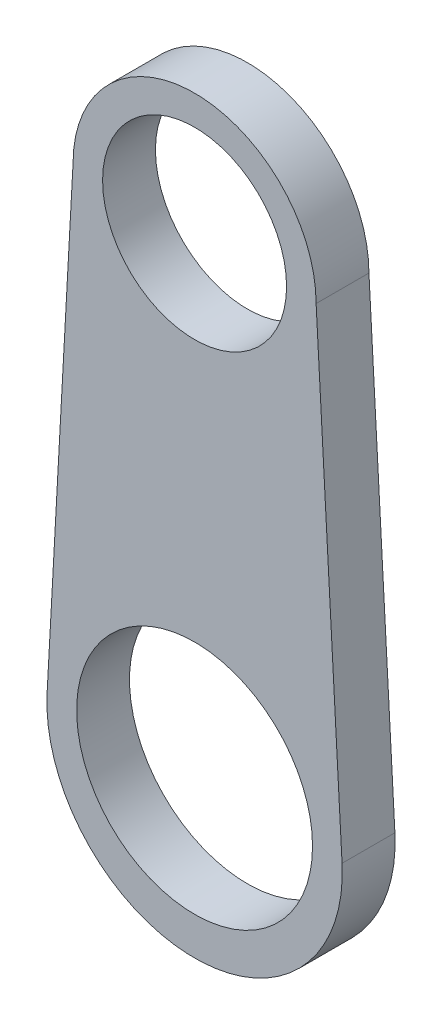
SolidWorks part; units mm, degrees
ref_plane "Front Plane" through (0, 0, 0) normal (0, 0, 1) x (1, 0, 0)
ref_plane "Top Plane" through (0, 0, 0) normal (0, 1, 0) x (1, 0, 0)
ref_plane "Right Plane" through (0, 0, 0) normal (1, 0, 0) x (0, 0, -1)
sketch "Sketch1" plane through (0, 0, 0) normal (0, 0, 1) x (1, 0, 0)
  line L0 (0, 0) -> (0, 50.8) construction
  line L1 (-12.7, 0) -> (-9.906, 50.8) construction
  line L2 (12.7, 0) -> (9.906, 50.8) construction
  line L3 (-13.0858, 50.8) -> (-15.8798, 0)
  line L4 (13.0858, 50.8) -> (15.8798, 0)
  line L5 (-15.8798, 0) -> (0, 0) construction
  line L6 (0, 0) -> (15.8798, 0) construction
  line L7 (-13.0858, 50.8) -> (0, 50.8) construction
  line L8 (0, 50.8) -> (13.0858, 50.8) construction
  circle A0 centre (0, 0) radius 12.7
  circle A1 centre (0, 50.8) radius 9.906
  arc A2 (-15.8798, 0) -> (15.8798, 0) centre (0, -0.8734) ccw
  arc A3 (-13.0858, 50.8) -> (13.0858, 50.8) centre (0, 50.8) cw
  dimension "D1" = 25.4
  dimension "D2" = 19.812
  dimension "D3" = 50.8
  dimension "D4" = 3.175
  dimension "D5" = 3.175
extrude "Boss-Extrude1" add sketch "Sketch1" along normal blind 5.6896 contours A3 L3 A2 L4 A1 A0
equation "\"w\"= 700"
equation "\"c to c\"= 2"
equation "\"top hole diameter\"= 0.780"
equation "\"bottom hole diameter\"= 1"
equation "\"MAXo\"= 45000"
equation "\"E\"= 10 * 10 ^ 6"
equation "\"maxd\"= 0.005"
equation "\"1\"= \"w\" * \"c to c\""
equation "\"2\"= \"E\" * \"maxd\""
equation "\"t\"= \"1\" / \"2\""
equation "\"D1@Sketch1\"=\"bottom hole diameter\""
equation "\"D2@Sketch1\"=\"top hole diameter\""
equation "\"D3@Sketch1\"=\"c to c\""
equation "\"offset arround hole\"= .125"
equation "\"thick\"= ( \"t\" ) / \"offset arround hole\""
equation "\"D4@Sketch1\"=\"offset arround hole\""
equation "\"D5@Sketch1\"=\"offset arround hole\""
equation "\"D1@Boss-Extrude1\"=\"thick\""
